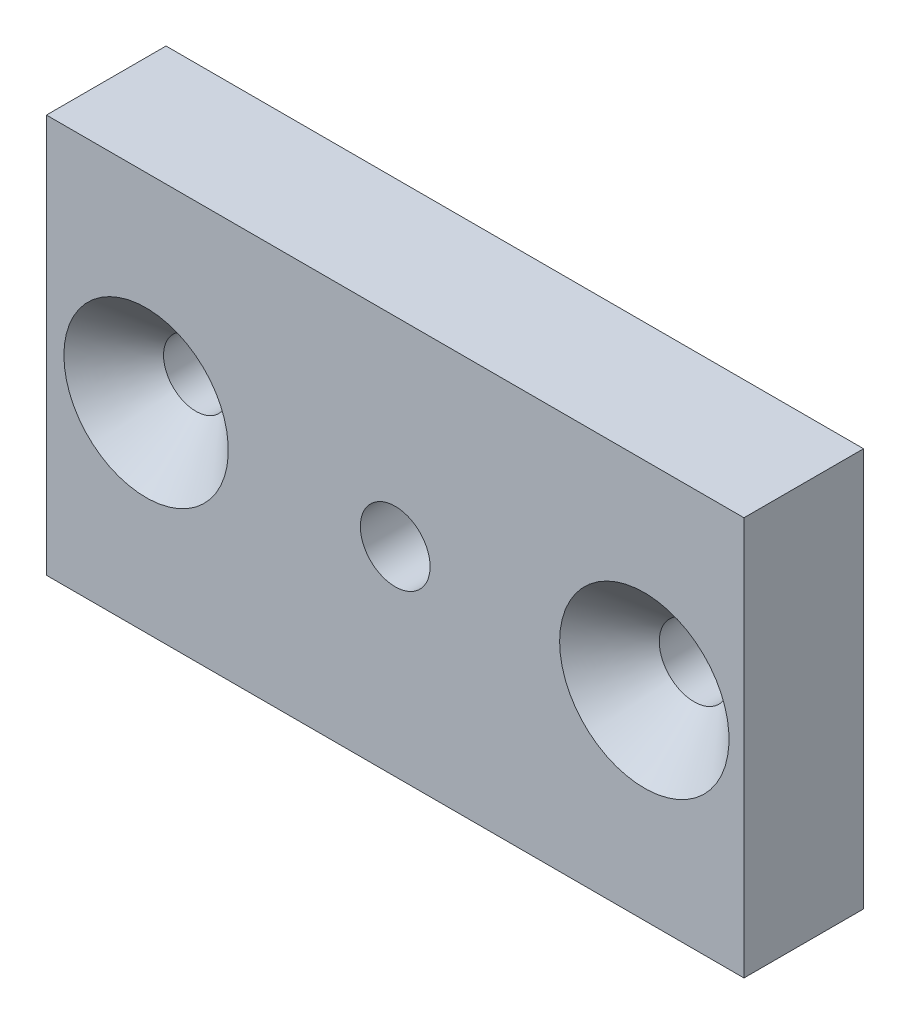
SolidWorks part; units mm, degrees
ref_plane "Front Plane" through (0, 0, 0) normal (0, 0, 1) x (1, 0, 0)
ref_plane "Top Plane" through (0, 0, 0) normal (0, 1, 0) x (1, 0, 0)
ref_plane "Right Plane" through (0, 0, 0) normal (1, 0, 0) x (0, 0, -1)
sketch "Sketch1" plane through (0, 0, 0) normal (0, 0, 1) x (1, 0, 0)
  line L1 (0, 0) -> (35, 0)
  line L2 (0, 0) -> (0, 20)
  line L3 (0, 20) -> (35, 20)
  line L4 (35, 0) -> (35, 20)
  circle A0 centre (5, 10) radius 1.625
  circle A1 centre (30, 10) radius 1.75
  circle A2 centre (17.5, 10) radius 1.75
  dimension "D3" = 10
  dimension "D4" = 10
  dimension "D5" = 5
  dimension "D6" = 5
  dimension "D7" = 3.25
  dimension "D8" = 3.5
  dimension "D9" = 3.5
  dimension "D10" = 17.5
  dimension "D11" = 10
  dimension "D1" = 35
  dimension "D2" = 20
extrude "Boss-Extrude1" add sketch "Sketch1" along normal blind 6
chamfer "Chamfer1" distance 2.5 angle 45 2 edges at (31.75, 10, 6) (6.625, 10, 6)
sketch "Sketch2" plane through (0, 0, 0) normal (0, 0, -1) x (-1, 0, 0)
  line L0 (0, 0) -> (-35, 0) construction
  line L1 (-19.3764, 13.25) -> (-21.2528, 10)
  line L2 (-21.2528, 10) -> (-19.3764, 6.75)
  line L3 (-19.3764, 6.75) -> (-15.6236, 6.75)
  line L4 (-15.6236, 6.75) -> (-13.7472, 10)
  line L5 (-13.7472, 10) -> (-15.6236, 13.25)
  line L6 (-15.6236, 13.25) -> (-19.3764, 13.25)
  circle A0 centre (-17.5, 10) radius 3.25 construction
  dimension "D1" = 0
  dimension "D2" = 6.5
extrude "Cut-Extrude1" cut sketch "Sketch2" against normal blind 2.5
